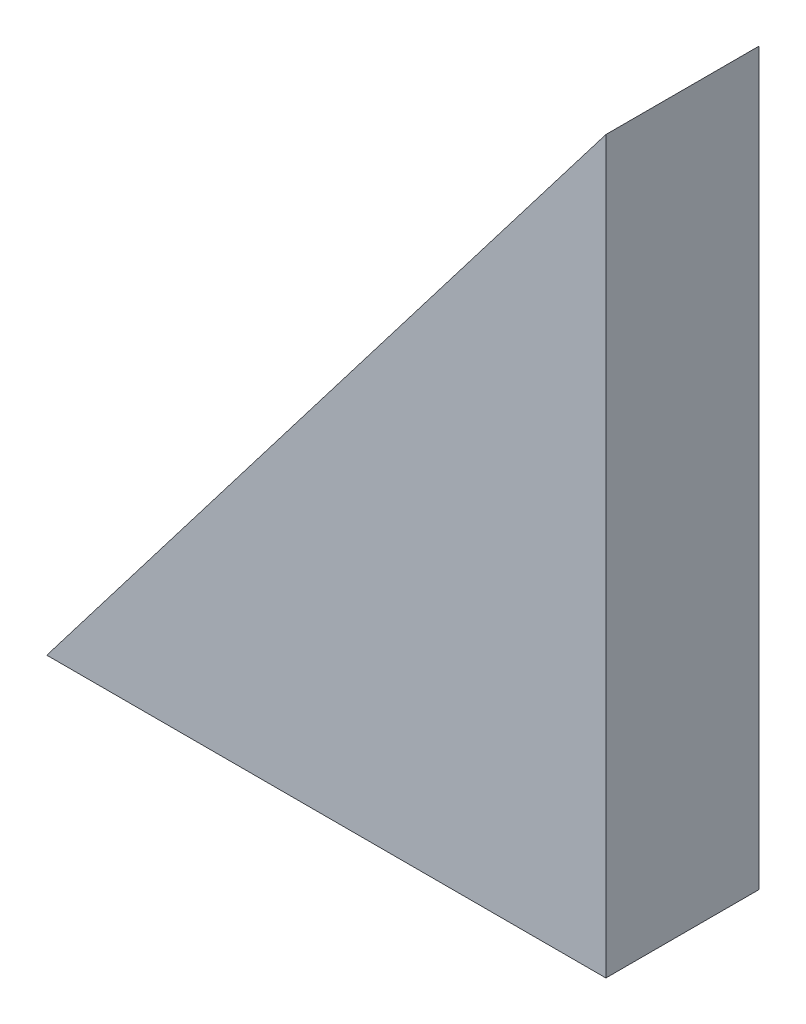
SolidWorks part; units mm, degrees
ref_plane "Front Plane" through (0, 0, 0) normal (0, 0, 1) x (1, 0, 0)
ref_plane "Top Plane" through (0, 0, 0) normal (0, 1, 0) x (1, 0, 0)
ref_plane "Right Plane" through (0, 0, 0) normal (1, 0, 0) x (0, 0, -1)
sketch "Sketch1" plane through (0, 0, 0) normal (0, 0, 1) x (1, 0, 0)
  line L0 (-953.6863, 60.5102) -> (49046.3137, 60.5102) construction
  line L1 (-46.4148, 60.5102) -> (30343.1707, 39765.3347) construction
  line L2 (-0.1011, -961.0603) -> (-0.1011, 49038.9397) construction
  line L3 (-46.4148, 60.5102) -> (-48.7685, 62.3116) construction
  line L4 (-0.1011, 121.0203) -> (-10.7678, 129.1845) construction
  line L5 (-0.1011, 121.0203) -> (-0.1011, 60.5102)
  line L6 (-0.1011, 60.5102) -> (-46.4148, 60.5102)
  line L7 (-46.4148, 60.5102) -> (-0.1011, 121.0203)
  dimension "D1" = 52.57
  dimension "D2" = 76.2
extrude "Extrude1" add sketch "Sketch1" along normal blind 12.7
